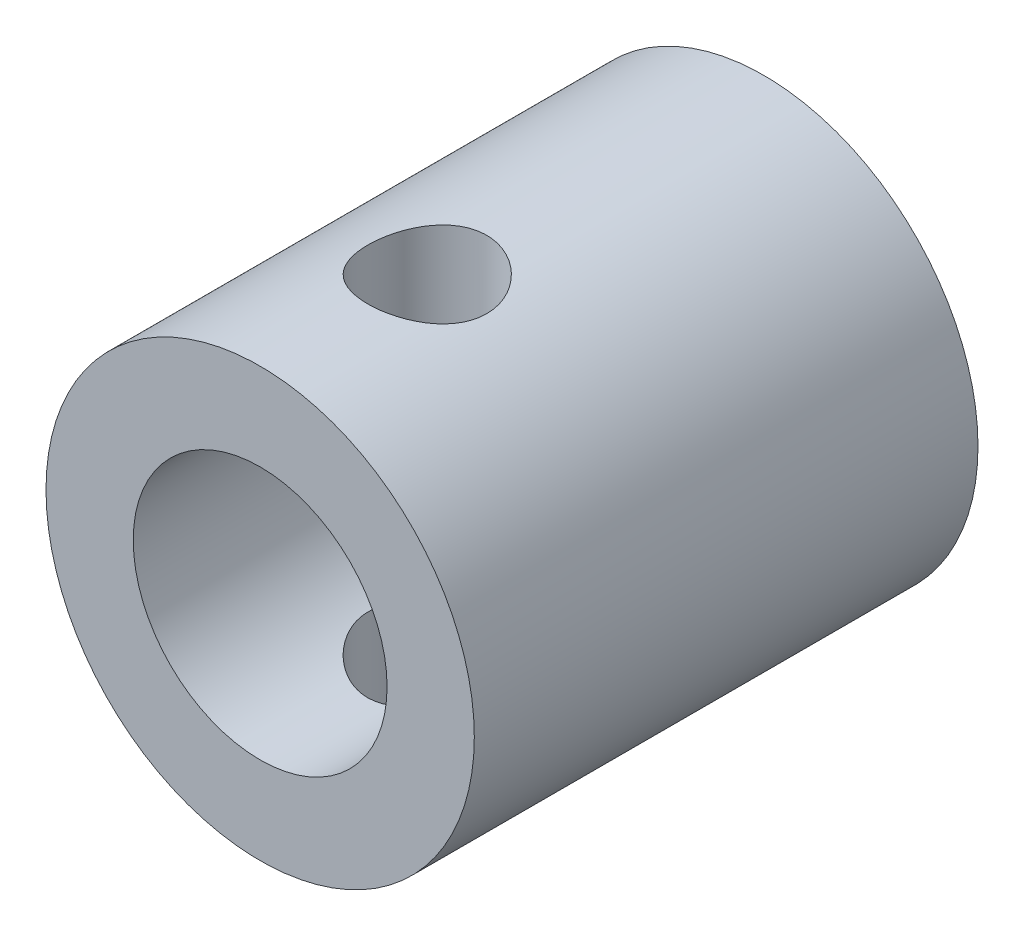
SolidWorks part; units mm, degrees
ref_plane "Front Plane" through (0, 0, 0) normal (0, 0, 1) x (1, 0, 0)
ref_plane "Top Plane" through (0, 0, 0) normal (0, 1, 0) x (1, 0, 0)
ref_plane "Right Plane" through (0, 0, 0) normal (1, 0, 0) x (0, 0, -1)
sketch "Sketch1" plane through (0, 0, 0) normal (0, 0, 1) x (1, 0, 0)
  circle A0 centre (0, 0) radius 5.4
  dimension "D1" = 10.8
extrude "Boss-Extrude1" add sketch "Sketch1" along normal blind 12.7
ref_plane "Plane1" through (0, 5.4, 0) normal (0, 1, 0) x (1, 0, 0)
sketch "Sketch3" plane through (0, 5.4, 0) normal (0, 1, 0) x (1, 0, 0)
  circle A1 centre (0, -8.4866) radius 1.5
  dimension "D1" = 3
extrude "Cut-Extrude2" cut sketch "Sketch3" against normal blind 12.7
sketch "Sketch4" plane through (0, 0, 12.7) normal (0, 0, 1) x (1, 0, 0)
  circle A0 centre (0, 0) radius 3.2
  dimension "D1" = 6.4
sketch "Sketch5" plane through (0, 0, 0) normal (0, 0, -1) x (-1, 0, 0)
  circle A0 centre (0, 0) radius 2.25
  dimension "D1" = 4.5
extrude "Cut-Extrude3" cut sketch "Sketch5" against normal blind 3.5
extrude "Cut-Extrude4" cut sketch "Sketch4" against normal blind 9.2
